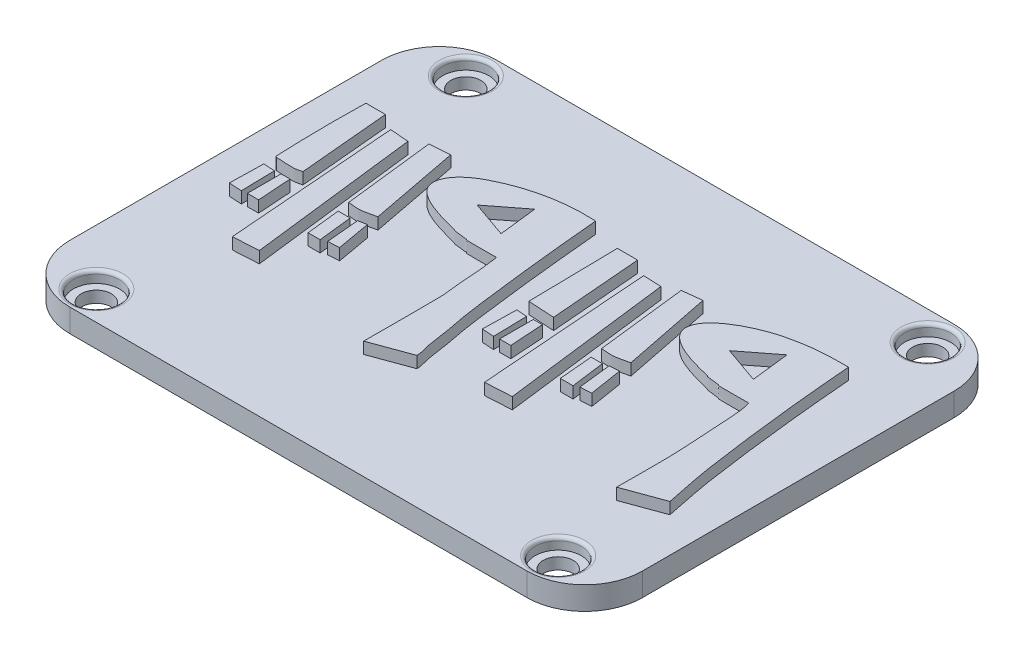
SolidWorks part; units mm, degrees
ref_plane "前视基准面" through (0, 0, 0) normal (0, 0, 1) x (1, 0, 0)
ref_plane "上视基准面" through (0, 0, 0) normal (0, 1, 0) x (1, 0, 0)
ref_plane "右视基准面" through (0, 0, 0) normal (1, 0, 0) x (0, 0, -1)
sketch "草图1" plane through (0, 0, 0) normal (0, 1, 0) x (1, 0, 0)
  line L1 (-24.8, 18.5) -> (24.8, 18.5)
  line L2 (-24.8, 18.5) -> (-24.8, -18.5)
  line L3 (-24.8, -18.5) -> (24.8, -18.5)
  line L4 (24.8, 18.5) -> (24.8, -18.5)
  line L5 (-24.8, 18.5) -> (24.8, -18.5) construction
  line L6 (-24.8, -18.5) -> (24.8, 18.5) construction
  point P0 (0, 0)
  dimension "D1" = 49.6
  dimension "D2" = 37
extrude "凸台-拉伸1" add sketch "草图1" along normal blind 2
fillet "圆角1" radius 5 4 edges at (-24.8, 1, 18.5) (24.8, 1, 18.5) (24.8, 1, -18.5) (-24.8, 1, -18.5)
sketch "草图2" plane through (0, 2, 0) normal (0, 1, 0) x (1, 0, 0)
  line L0 (0, 18.5) -> (0, -18.5) construction
  line L1 (19.8, 18.5) -> (-19.8, 18.5) construction
  line L2 (-19.8, -18.5) -> (19.8, -18.5) construction
  line L3 (-24.8, 0) -> (24.8, 0) construction
  line L4 (-24.8, 13.5) -> (-24.8, -13.5) construction
  line L5 (24.8, -13.5) -> (24.8, 13.5) construction
  circle A0 centre (-20, 16) radius 1.3
  circle A1 centre (-20, -16) radius 1.3
  circle A2 centre (20, -16) radius 1.3
  circle A3 centre (20, 16) radius 1.3
  dimension "D1" = 2.6
  dimension "D2" = 20
  dimension "D3" = 16
extrude "切除-拉伸1" cut sketch "草图2" against normal up to next
sketch "草图3" plane through (0, 2, 0) normal (0, 1, 0) x (1, 0, 0)
  line L0 (0, 18.5) -> (0, -18.5) construction
  line L1 (19.8, 18.5) -> (-19.8, 18.5) construction
  line L2 (-19.8, -18.5) -> (19.8, -18.5) construction
  line L3 (-24.8, 0) -> (24.8, 0) construction
  line L4 (-24.8, 13.5) -> (-24.8, -13.5) construction
  line L5 (24.8, -13.5) -> (24.8, 13.5) construction
  circle A0 centre (-20, 16) radius 2
  circle A1 centre (20, 16) radius 2
  circle A2 centre (20, -16) radius 2
  circle A3 centre (-20, -16) radius 2
  dimension "D1" = 4
extrude "切除-拉伸2" cut sketch "草图3" against normal blind 1
fillet "圆角2" radius 0.3 4 edges at (-20, 2, -14) (20, 2, 18) (20, 2, -18) (-20, 2, 14)
sketch "草图4" plane through (0, 2, 0) normal (0, 1, 0) x (1, 0, 0)
  line L0 (104.0255, 249.5814) -> (591.0903, 249.5814) construction
  line L1 (-161.744, -48.2462) -> (303.5893, -48.2462) construction
  line L2 (92.9791, 169.5232) -> (558.3124, 169.5232) construction
  line L3 (94.2355, 163.8986) -> (559.5689, 163.8986) construction
  line L4 (21.7728, -8.0954) -> (18.3925, -9.3305)
  line L5 (-0.1342, -8.0954) -> (-3.5145, -9.3305)
  line L6 (7.0814, -7.0553) -> (4.8062, -7.1853)
  line L7 (4.8062, -7.1853) -> (3.7011, 7.7011)
  line L8 (3.7011, 7.7011) -> (5.2613, 7.636)
  line L9 (5.2613, 7.636) -> (7.0814, -7.0553)
  line L10 (-14.8256, -7.0553) -> (-17.0358, -7.1853)
  line L11 (-17.0358, -7.1853) -> (-18.2059, 7.7011)
  line L12 (-18.2059, 7.7011) -> (-16.5807, 7.571)
  line L13 (8.9016, -3.61) -> (7.7965, -3.61)
  line L14 (7.7965, -3.61) -> (7.5365, -0.6847)
  line L15 (8.5116, -0.6847) -> (8.9016, -3.61)
  line L16 (-13.0054, -3.61) -> (-14.0455, -3.61)
  line L17 (-14.0455, -3.61) -> (-14.3705, -0.6847)
  line L18 (-14.3705, -0.6847) -> (-13.3304, -0.6847)
  line L19 (-13.3304, -0.6847) -> (-13.0054, -3.61)
  line L20 (9.2916, -3.415) -> (8.9666, -0.5547)
  line L21 (9.8117, -0.4897) -> (10.2667, -3.35)
  line L22 (-12.5504, -3.415) -> (-12.8104, -0.5547)
  line L23 (-12.0953, -0.4247) -> (-11.5753, -3.35)
  line L24 (2.206, -3.285) -> (2.206, -0.3597)
  line L25 (2.9861, -0.3597) -> (3.1811, -3.285)
  line L26 (1.751, -3.35) -> (0.7109, -3.285)
  line L27 (0.7109, -3.285) -> (0.7759, -0.3597)
  line L28 (1.6859, -0.4247) -> (1.751, -3.35)
  line L29 (-19.636, -3.285) -> (-19.636, -0.3597)
  line L30 (-18.8559, -0.3597) -> (-18.6609, -3.285)
  line L31 (-20.091, -3.35) -> (-21.1961, -3.285)
  line L32 (-21.1961, -3.285) -> (-21.1311, -0.3597)
  line L33 (-20.1561, -0.4247) -> (-20.091, -3.35)
  line L34 (7.3415, 0.4204) -> (6.4314, 8.2211)
  line L35 (6.4314, 8.2211) -> (8.1215, 8.4161)
  line L36 (8.1215, 8.4161) -> (9.6817, 0.6154)
  line L37 (-14.5655, 0.4204) -> (-15.4756, 8.2861)
  line L38 (-15.4756, 8.2861) -> (-13.7205, 8.4161)
  line L39 (-13.7205, 8.4161) -> (-12.2253, 0.6154)
  line L40 (2.9211, 0.6804) -> (0.6458, 0.8104)
  line L41 (0.6458, 0.8104) -> (0.5158, 8.6111)
  line L42 (0.5158, 8.6111) -> (2.271, 8.6111)
  line L43 (2.271, 8.6111) -> (2.9211, 0.6804)
  line L44 (-21.2612, 8.6111) -> (-19.571, 8.6111)
  line L45 (-19.571, 8.6111) -> (-18.8559, 0.7454)
  line L46 (-11.5753, -3.35) -> (-12.5504, -3.415)
  line L47 (-12.0953, -0.4247) -> (-12.8104, -0.5547)
  line L48 (-18.6609, -3.285) -> (-19.636, -3.285)
  line L49 (-19.636, -0.3597) -> (-18.8559, -0.3597)
  line L50 (-5.622, 4.6749) -> (-6.0036, 7.9728)
  line L51 (-6.0036, 7.9728) -> (-8.8079, 5.7913)
  line L52 (-8.8079, 5.7913) -> (-5.622, 4.6749)
  line L53 (16.2279, 4.6749) -> (15.8464, 7.9728)
  line L54 (15.8464, 7.9728) -> (13.0421, 5.7913)
  line L55 (13.0421, 5.7913) -> (16.2279, 4.6749)
  line L56 (9.2916, -3.415) -> (10.2667, -3.35)
  line L57 (9.8117, -0.4897) -> (8.9666, -0.5547)
  line L58 (7.5365, -0.6847) -> (8.5116, -0.6847)
  line L59 (3.1811, -3.285) -> (2.206, -3.285)
  line L60 (2.206, -0.3597) -> (2.9861, -0.3597)
  line L61 (-20.1561, -0.4247) -> (-21.1311, -0.3597)
  line L62 (-16.5807, 7.571) -> (-14.8256, -7.0553)
  line L63 (0.7759, -0.3597) -> (1.6859, -0.4247)
  line L64 (0, 18.5) -> (0, -18.5) construction
  line L65 (19.8, 18.5) -> (-19.8, 18.5) construction
  line L66 (-19.8, -18.5) -> (19.8, -18.5) construction
  line L67 (-24.8, 0) -> (24.8, 0) construction
  line L68 (-24.8, 13.5) -> (-24.8, -13.5) construction
  line L69 (24.8, -13.5) -> (24.8, 13.5) construction
  spline S0 degree 3 poles (18.3925, -9.3305) (18.3925, -7.2719) (18.4559, -5.2096) (18.3275, -3.1549) (18.2841, -2.4615) (18.2568, -1.767) (18.1975, -1.0747) (18.1179, -0.1464) (18.1294, 1.7295) (17.8074, 2.6956) knots 0 0 0 0 1 1 1 2 2 2 3 3 3 3
  spline S1 degree 3 poles (17.8074, 2.6956) (16.9407, 2.6956) (16.0737, 2.6745) (15.2072, 2.6956) (15.1765, 2.6963) (15.1724, 2.7556) (15.1422, 2.7606) (14.7763, 2.8216) (14.4029, 2.8296) (14.0371, 2.8906) (14.0068, 2.8957) (14.0018, 2.9482) (13.9721, 2.9556) (12.8735, 3.2303) (9.3359, 3.9711) (9.4217, 5.6859) (9.5106, 7.464) (12.9207, 8.8667) (14.3621, 9.1962) (14.9007, 9.3193) (15.4415, 9.4356) (15.9873, 9.5212) (17.1236, 9.6995) (18.2823, 9.7162) (19.4326, 9.7162) knots 0 0 0 0 1 1 1 2 2 2 3 3 3 4 4 4 5 5 5 6 6 6 7 7 7 8 8 8 8
  spline S2 degree 3 poles (19.4326, 9.7162) (19.8069, 5.0747) (20.299, 0.5133) (20.9927, -4.065) (21.1684, -5.2244) (21.5551, -6.9344) (21.7728, -8.0954) knots 0 0 0 0 1 1 1 2 2 2 2
  spline S3 degree 3 poles (-3.5145, -9.3305) (-3.5145, -7.0986) (-3.4931, -4.8667) (-3.5145, -2.6349) (-3.5189, -2.1812) (-3.6681, -1.1688) (-3.7095, -0.6847) (-3.7746, 0.0737) (-3.7794, 0.8397) (-3.9046, 1.5905) (-3.9655, 1.9564) (-3.9912, 2.3272) (-4.0346, 2.6956) knots 0 0 0 0 1 1 1 2 2 2 3 3 3 4 4 4 4
  spline S4 degree 3 poles (-4.0346, 2.6956) (-4.9013, 2.6956) (-5.7683, 2.6745) (-6.6348, 2.6956) (-6.6655, 2.6963) (-6.6696, 2.7558) (-6.6998, 2.7606) (-7.0875, 2.8218) (-7.4823, 2.8294) (-7.8699, 2.8906) (-7.9002, 2.8954) (-7.9054, 2.9476) (-7.9349, 2.9556) (-9.0743, 3.2664) (-12.3292, 3.9409) (-12.4203, 5.4908) (-12.4862, 6.6099) (-11.2925, 7.5483) (-10.4052, 8.0261) (-8.0049, 9.3185) (-5.1863, 9.8758) (-2.4744, 9.7162) knots 0 0 0 0 1 1 1 2 2 2 3 3 3 4 4 4 5 5 5 6 6 6 7 7 7 7
  spline S5 degree 3 poles (-2.4744, 9.7162) (-2.1015, 5.5518) (-1.6814, 1.549) (-1.1093, -2.5699) (-1.0306, -3.1363) (-0.8247, -4.1355) (-0.7193, -4.7151) (-0.5937, -5.4056) (-0.5198, -6.1048) (-0.3942, -6.7953) (-0.3293, -7.1524) (-0.1342, -7.6845) (-0.1342, -8.0954) knots 0 0 0 0 1 1 1 2 2 2 3 3 3 4 4 4 4
  spline S7 degree 3 poles (9.6817, 0.6154) (9.2483, 0.5287) (8.822, 0.3921) (8.3816, 0.3554) (8.0354, 0.3265) (7.6882, 0.3987) (7.3415, 0.4204) knots 0 0 0 0 1 1 1 2 2 2 2
  spline S8 degree 3 poles (-12.2253, 0.6154) (-12.6587, 0.5287) (-13.085, 0.3921) (-13.5254, 0.3554) (-13.8716, 0.3265) (-14.2188, 0.3987) (-14.5655, 0.4204) knots 0 0 0 0 1 1 1 2 2 2 2
  spline S9 degree 3 poles (-18.8559, 0.7454) (-19.0949, 0.7056) (-19.3287, 0.6154) (-19.571, 0.6154) (-20.0698, 0.6154) (-20.569, 0.639) (-21.0661, 0.6804) (-21.1272, 0.6855) (-21.194, 0.7492) (-21.1961, 0.8104) (-21.2858, 3.4092) (-21.3376, 6.0119) (-21.2612, 8.6111) knots 0 0 0 0 1 1 1 2 2 2 3 3 3 4 4 4 4
  point P89 (0, 0)
extrude "凸台-拉伸2" add sketch "草图4" along normal blind 1
